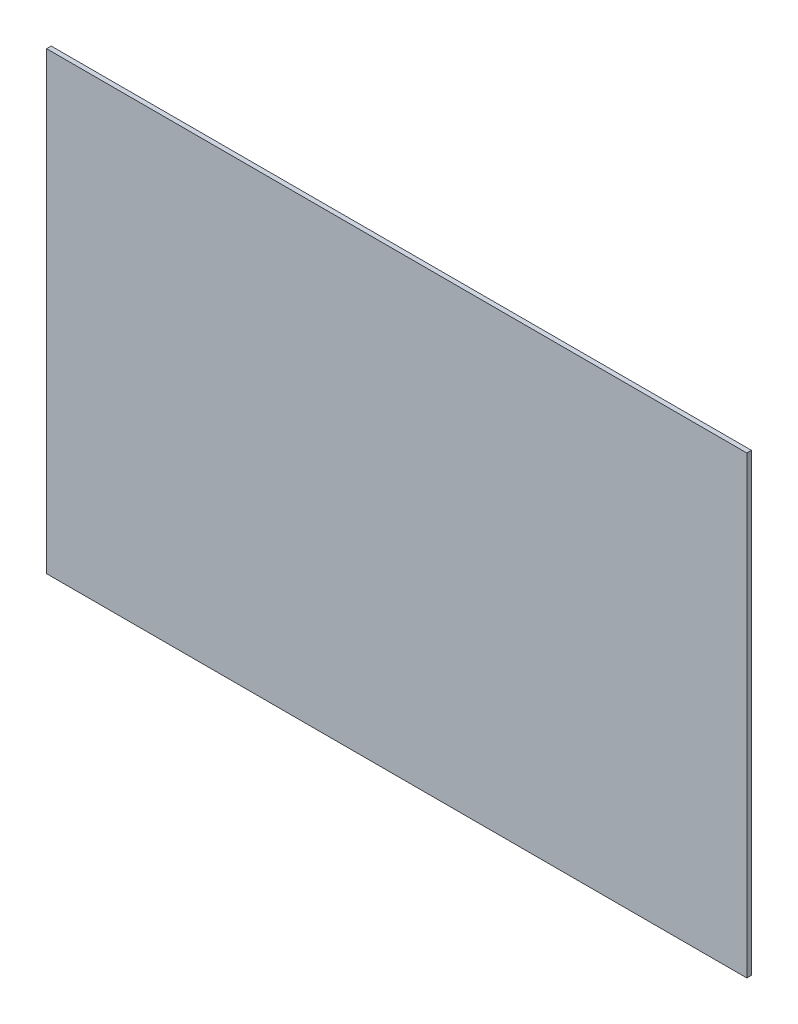
SolidWorks part; units mm, degrees
ref_plane "Front Plane" through (0, 0, 0) normal (0, 0, 1) x (1, 0, 0)
ref_plane "Top Plane" through (0, 0, 0) normal (0, 1, 0) x (1, 0, 0)
ref_plane "Right Plane" through (0, 0, 0) normal (1, 0, 0) x (0, 0, -1)
sketch "Sketch2" plane through (0, 0, 0) normal (0, 0, 1) x (1, 0, 0)
  line L1 (0, 0) -> (1500, 0)
  line L2 (0, 0) -> (0, 500)
  line L3 (0, 500) -> (1500, 500)
  line L4 (1500, 0) -> (1500, 500)
  dimension "D1" = 1500
  dimension "D2" = 500
extrude "Boss-Extrude1" add sketch "Sketch2" along normal blind 10
sketch "Sketch3" plane through (0, 0, 10) normal (0, 0, 1) x (1, 0, 0)
  line L1 (0, 500) -> (3000, 500)
  line L2 (0, 500) -> (0, -1500)
  line L3 (0, -1500) -> (3000, -1500)
  line L4 (3000, 500) -> (3000, -1500)
  dimension "D1" = 3000
  dimension "D2" = 2000
extrude "Boss-Extrude2" add sketch "Sketch3" against normal blind 10
sketch "Sketch4" plane through (0, 0, 10) normal (0, 0, 1) x (1, 0, 0)
  line L1 (0, -1500) -> (1517.1, -1500)
  line L2 (0, -1500) -> (0, -515)
  line L3 (0, -515) -> (1517.1, -515)
  line L4 (1517.1, -1500) -> (1517.1, -515)
  line L5 (0, 500) -> (3000, 500)
  line L6 (0, 500) -> (0, -1500)
  line L7 (0, -1500) -> (3000, -1500)
  line L8 (3000, 500) -> (3000, -1500)
  line M7 (0, 500) -> (0, -1500)
  line M8 (0, -1500) -> (3000, -1500)
  line M9 (3000, -1500) -> (3000, 500)
  line M10 (3000, 500) -> (0, 500)
  dimension "D1" = 1517.1
  dimension "D2" = 985
extrude "Cut-Extrude1" cut sketch "Sketch4" against normal blind 10 contours L4 L3 M8 M9 M10 M7
